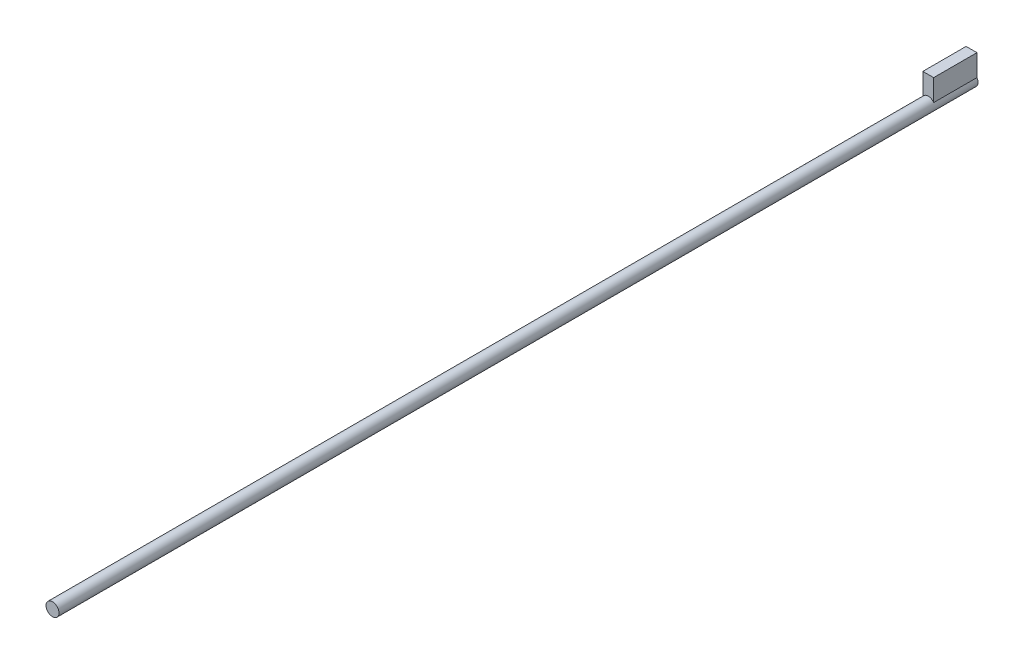
SolidWorks part; units mm, degrees
ref_plane "Front Plane" through (0, 0, 0) normal (0, 0, 1) x (1, 0, 0)
ref_plane "Top Plane" through (0, 0, 0) normal (0, 1, 0) x (1, 0, 0)
ref_plane "Right Plane" through (0, 0, 0) normal (1, 0, 0) x (0, 0, -1)
sketch "Sketch1" plane through (0, 0, 0) normal (0, 0, 1) x (1, 0, 0)
  circle A0 centre (0, 0) radius 1.5
  dimension "D1" = 3
extrude "Boss-Extrude1" add sketch "Sketch1" along normal blind 212.4
sketch "Sketch2" plane through (0, 0, 0) normal (0, 0, -1) x (-1, 0, 0)
  line L0 (-1.25, 0.8292) -> (1.25, 0.8292)
  line L1 (-1.25, 0.8292) -> (-1.25, 5.8292)
  line L2 (1.25, 0.8292) -> (1.25, 5.8292)
  line L3 (-1.25, 5.8292) -> (1.25, 5.8292)
  circle A1 centre (0, 0) radius 1.5
  circle A2 centre (0, 0) radius 1.5
  circle M6 centre (0, 0) radius 1.5
  dimension "D2" = 2.5
  dimension "D3" = 5
  dimension "D1" = 0
extrude "Boss-Extrude2" add sketch "Sketch2" against normal blind 10 contours L3 L1 L2 M6
